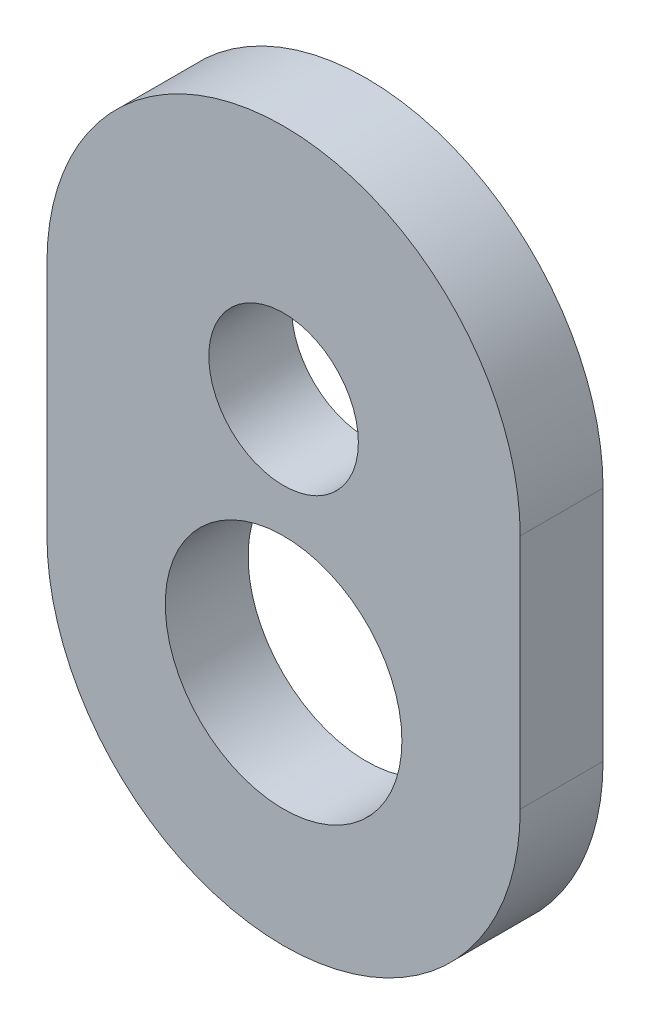
SolidWorks part; units mm, degrees
material "Titanium"
ref_plane "Front Plane" through (0, 0, 0) normal (0, 0, 1) x (1, 0, 0)
ref_plane "Top Plane" through (0, 0, 0) normal (0, 1, 0) x (1, 0, 0)
ref_plane "Right Plane" through (0, 0, 0) normal (1, 0, 0) x (0, 0, -1)
sketch "Sketch1" plane through (0, 0, 0) normal (0, 0, 1) x (1, 0, 0)
  line L0 (0, 0) -> (0, 25.4)
  line L2 (50.8, 25.4) -> (50.8, 0)
  arc A0 (0, 25.4) -> (50.8, 25.4) centre (25.4, 25.4) cw
  arc A1 (50.8, 0) -> (0, 0) centre (25.4, 0) cw
  dimension "D1" = 76.2
  dimension "D2" = 50.8
extrude "Boss-Extrude1" add sketch "Sketch1" along normal blind 8.89
sketch "Sketch2" plane through (0, 0, 8.89) normal (0, 0, 1) x (1, 0, 0)
  line L0 (25.4, 50.8) -> (25.4, -25.4) construction
  line L1 (0, 25.4) -> (50.8, 25.4) construction
  line L2 (0, 0) -> (50.8, 0) construction
  arc A1 (50.8, 25.4) -> (0, 25.4) centre (25.4, 25.4) ccw construction
  arc A2 (0, 0) -> (50.8, 0) centre (25.4, 0) ccw construction
  circle A3 centre (25.4, 0) radius 12.7
  circle A4 centre (25.4, 25.4) radius 8.0264
  point P20 (25.4, 25.4)
  dimension "D1" = 16.0528
  dimension "D2" = 25.4
extrude "Cut-Extrude2" cut sketch "Sketch2" against normal through all
equation "\"L\"= 4in"
equation "\"F\"= 650"
equation "\"W\"= 2in"
equation "\"WT\"= 1in"
equation "\"SY\"= 120091"
equation "\"SF\"= 4"
equation "\"T\"= ( \"F\" * \"SF\" ) / ( \"WT\" * \"SY\" )"
equation "\"D1@Sketch1\"=3"
equation "\"D2@Sketch1\"= \"W\""
equation "\"D1@Boss-Extrude1\"=.35"
